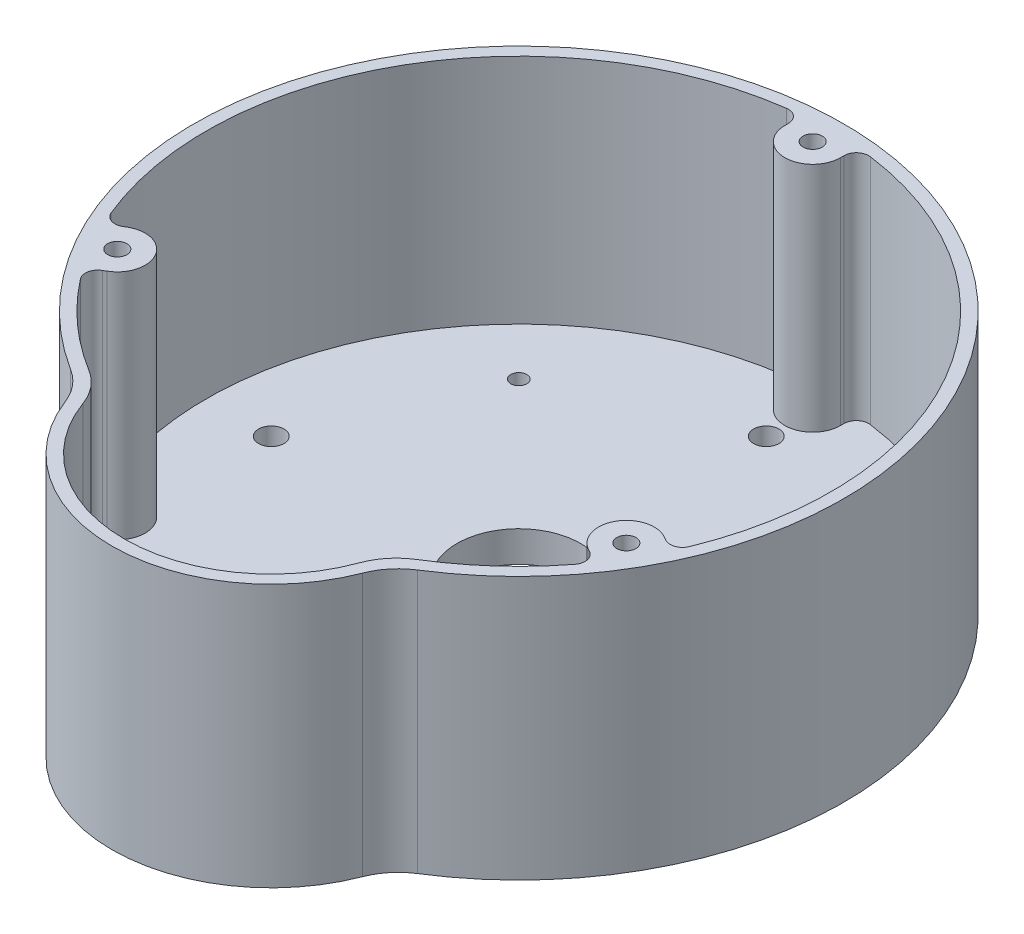
SolidWorks part; units mm, degrees
ref_plane "Plan de face" through (0, 0, 0) normal (0, 0, 1) x (1, 0, 0)
ref_plane "Plan de dessus" through (0, 0, 0) normal (0, 1, 0) x (1, 0, 0)
ref_plane "Plan de droite" through (0, 0, 0) normal (1, 0, 0) x (0, 0, -1)
sketch "Esquisse1" plane through (0, 0, 0) normal (0, 1, 0) x (1, 0, 0)
  line L0 (-51.4386, 28) -> (54.7147, 28) construction
  line L1 (-93.9383, 0) -> (92.9837, 0) construction
  line L2 (0, 84.3142) -> (0, -27.4159) construction
  line L3 (-79.8999, -42) -> (100.4836, -42) construction
  circle A0 centre (0, 0) radius 52.5
  circle A1 centre (0, 40) radius 2.05
  circle A2 centre (40, 0) radius 2.05
  circle A3 centre (0, -40) radius 2.05
  circle A4 centre (-40, 0) radius 2.05
  circle A5 centre (28, 28) radius 1.3
  circle A6 centre (20, -42) radius 1.3
  circle A7 centre (-20, -42) radius 1.3
  circle A8 centre (-28, 28) radius 1.3
  circle A9 centre (0, 0) radius 10
  point P14 (0, 0)
  dimension "D1" = 105
  dimension "D2" = 4.1
  dimension "D7" = 56
  dimension "D9" = 20
  dimension "D10" = 2.6
  dimension "D4" = 40
  dimension "D5" = 28
  dimension "D6" = 42
  dimension "D8" = 40
  dimension "D3" = 4
extrude "Boss.-Extru.2" add sketch "Esquisse1" along normal blind 5
sketch "Esquisse2" plane through (0, 5, 0) normal (0, 1, 0) x (1, 0, 0)
  line L0 (0, 90.2757) -> (0, -93.0238) construction
  line L1 (-4.5, 47.5) -> (-4.5, 50.2991) construction
  line L2 (4.5, 47.5) -> (4.5, 50.2991) construction
  line L3 (0, 0) -> (-88.0909, 50.8593) construction
  line L4 (0, 0) -> (91.089, 52.5902) construction
  line L5 (-4.5, 47.5) -> (-4.5, 48.0625)
  line L6 (4.5, 48.0625) -> (4.5, 47.5)
  line L7 (43.3862, -19.8529) -> (43.8733, -20.1341)
  line L8 (39.3733, -27.9283) -> (38.8862, -27.6471)
  line L9 (-38.8862, -27.6471) -> (-39.3733, -27.9283)
  line L10 (-43.8733, -20.1341) -> (-43.3862, -19.8529)
  circle A0 centre (0, 0) radius 50.5 construction
  circle A1 centre (0, 0) radius 52.5
  circle A2 centre (0, 0) radius 52.5
  circle A3 centre (0, 47.5) radius 4.5
  circle A4 centre (41.1362, -23.75) radius 4.5
  circle A5 centre (-41.1362, -23.75) radius 4.5
  arc A6 (-6.768, 50.0444) -> (-43.7343, 25.25) centre (0, 0) ccw
  arc A7 (6.768, 50.0444) -> (43.7343, 25.25) centre (0, 0) cw
  arc A8 (4.5, 48.0625) -> (6.768, 50.0444) centre (6.5, 48.0625) cw
  arc A9 (-6.768, 50.0444) -> (-4.5, 48.0625) centre (-6.5, 48.0625) cw
  arc A10 (46.7238, -19.1609) -> (43.7343, 25.25) centre (0, 0) ccw
  arc A11 (39.9557, -30.8835) -> (0, -50.5) centre (0, 0) cw
  arc A12 (39.3733, -27.9283) -> (39.9557, -30.8835) centre (38.3733, -29.6604) cw
  arc A13 (46.7238, -19.1609) -> (43.8733, -20.1341) centre (44.8733, -18.4021) cw
  arc A14 (-39.9557, -30.8835) -> (0, -50.5) centre (0, 0) ccw
  arc A15 (-46.7238, -19.1609) -> (-43.7343, 25.25) centre (0, 0) cw
  arc A16 (-43.8733, -20.1341) -> (-46.7238, -19.1609) centre (-44.8733, -18.4021) cw
  arc A17 (-39.9557, -30.8835) -> (-39.3733, -27.9283) centre (-38.3733, -29.6604) cw
  point P28 (0, 0)
  point P51 (0, 0)
  circle M7 centre (0, 0) radius 52.5
  dimension "D2" = 2
  dimension "D3" = 9
  dimension "D4" = 47.5
  dimension "D6" = 60
  dimension "D8" = 2
  dimension "D7" = 60
  dimension "D1" = 0
  dimension "D5" = 3
  dimension "D9" = 3
extrude "Boss.-Extru.3" add sketch "Esquisse2" along normal blind 37.5 contours A5 | A3 | A4 | A14 A17 L9 A5 L10 A16 A15 A6 A9 L5 A3 L6 A8 A7 A10 A13 L7 A4 L8 A12 A11 M7 | A2
sketch "Esquisse3" plane through (0, 42.5, 0) normal (0, 1, 0) x (1, 0, 0)
  circle A0 centre (0, 47.5) radius 3.35
  circle A3 centre (41.1362, -23.75) radius 3.35
  circle A4 centre (-41.1362, -23.75) radius 3.35
  circle A9 centre (0, 0) radius 52.5
  circle A10 centre (0, 0) radius 52.5
  point P13 (0, 0)
  dimension "D2" = 3
  dimension "D3" = 6.7
  dimension "D1" = 0
extrude "Enlèv. mat.-Extru.1" cut sketch "Esquisse3" against normal through all from offset 4 contours A0 | A4 | A3 offset against normal yes
sketch "Esquisse5" plane through (0, 42.5, 0) normal (0, 1, 0) x (1, 0, 0)
  arc A0 (-4.5, 47.5) -> (4.5, 47.5) centre (0, 47.5) ccw construction
  arc A1 (-4.5, 47.5) -> (4.5, 47.5) centre (0, 47.5) ccw
  circle A2 centre (0, 47.5) radius 1.55
  circle A3 centre (41.1362, -23.75) radius 1.55
  circle A4 centre (-41.1362, -23.75) radius 1.55
  point P11 (0, 0)
  dimension "D1" = 3.1
  dimension "D2" = 3
extrude "Enlèv. mat.-Extru.3" cut sketch "Esquisse5" against normal through all contours A4 | A3 | A2
sketch "Esquisse6" plane through (0, 0, 0) normal (0, -1, 0) x (1, 0, 0)
  circle A0 centre (-20, 42) radius 3.75
  circle A1 centre (0, 0) radius 52.5
  circle A3 centre (20, 42) radius 3.75
  circle A4 centre (-28, -28) radius 3.75
  circle A5 centre (28, -28) radius 3.75
  circle A15 centre (0, 0) radius 52.5
  dimension "D2" = 7.5
  dimension "D1" = 0
extrude "Enlèv. mat.-Extru.4" cut sketch "Esquisse6" against normal blind 3 contours A0 | A3 | A5 | A4
sketch "Esquisse7" plane through (0, 0, 0) normal (0, 0, 1) x (1, 0, 0)
  line L0 (0, 56.3049) -> (0, -34.4214) construction
  line L1 (-52.5, 0) -> (52.5, 0) construction
  line L2 (-52.5, 0) -> (52.5, 0)
  line L3 (52.5, 42.5) -> (-52.5, 42.5) construction
  line L4 (52.5, 42.5) -> (-52.5, 42.5)
  line L5 (-25, 42.5) -> (-25, 5)
  line L6 (-25, 5) -> (25, 5)
  line L7 (25, 5) -> (25, 42.5)
  line L8 (-25, 42.5) -> (25, 42.5)
  dimension "D1" = 5
  dimension "D2" = 25
extrude "Enlèv. mat.-Extru.5" cut sketch "Esquisse7" along normal through all contours L0 L8 L5 L6 | L4 L0 L6 L7
sketch "Esquisse8" plane through (0, 0, 0) normal (0, 1, 0) x (1, 0, 0)
  line L0 (0, 4.2422) -> (0, -58.8142) construction
  line L6 (25, -46.1655) -> (25, -43.8777)
  line L7 (25, -46.1655) -> (25, -43.8777)
  line L8 (-38.8862, -27.6471) -> (-39.3733, -27.9283)
  line L9 (-38.8862, -27.6471) -> (-39.3733, -27.9283)
  line L10 (-25, -43.8777) -> (-25, -46.1655)
  line L11 (-25, -43.8777) -> (-25, -46.1655)
  line L12 (39.3733, -27.9283) -> (38.8862, -27.6471)
  line L13 (39.3733, -27.9283) -> (38.8862, -27.6471)
  line L25 (43.3862, -19.8529) -> (43.8733, -20.1341)
  line L26 (43.3862, -19.8529) -> (43.8733, -20.1341)
  line L27 (4.5, 48.0625) -> (4.5, 47.5)
  line L28 (4.5, 48.0625) -> (4.5, 47.5)
  line L29 (-4.5, 47.5) -> (-4.5, 48.0625)
  line L30 (-4.5, 47.5) -> (-4.5, 48.0625)
  line L31 (-43.8733, -20.1341) -> (-43.3862, -19.8529)
  line L32 (-43.8733, -20.1341) -> (-43.3862, -19.8529)
  arc A2 (-25, -46.1655) -> (25, -46.1655) centre (0, -40) ccw
  arc A4 (39.9557, -30.8835) -> (39.3733, -27.9283) centre (38.3733, -29.6604) ccw
  arc A11 (39.9557, -30.8835) -> (39.3733, -27.9283) centre (38.3733, -29.6604) ccw
  arc A12 (-39.3733, -27.9283) -> (-39.9557, -30.8835) centre (-38.3733, -29.6604) ccw
  arc A13 (-39.3733, -27.9283) -> (-39.9557, -30.8835) centre (-38.3733, -29.6604) ccw
  arc A14 (25, -43.8777) -> (39.9557, -30.8835) centre (0, 0) ccw
  arc A15 (25, -43.8777) -> (39.9557, -30.8835) centre (0, 0) ccw
  arc A16 (43.3862, -19.8529) -> (38.8862, -27.6471) centre (41.1362, -23.75) ccw
  arc A17 (43.3862, -19.8529) -> (38.8862, -27.6471) centre (41.1362, -23.75) ccw
  arc A18 (43.8733, -20.1341) -> (46.7238, -19.1609) centre (44.8733, -18.4021) ccw
  arc A19 (43.8733, -20.1341) -> (46.7238, -19.1609) centre (44.8733, -18.4021) ccw
  arc A20 (46.7238, -19.1609) -> (6.768, 50.0444) centre (0, 0) ccw
  arc A21 (46.7238, -19.1609) -> (6.768, 50.0444) centre (0, 0) ccw
  arc A22 (6.768, 50.0444) -> (4.5, 48.0625) centre (6.5, 48.0625) ccw
  arc A23 (6.768, 50.0444) -> (4.5, 48.0625) centre (6.5, 48.0625) ccw
  arc A24 (-4.5, 47.5) -> (4.5, 47.5) centre (0, 47.5) ccw
  arc A25 (-4.5, 47.5) -> (4.5, 47.5) centre (0, 47.5) ccw
  arc A48 (-4.5, 48.0625) -> (-6.768, 50.0444) centre (-6.5, 48.0625) ccw
  arc A49 (-4.5, 48.0625) -> (-6.768, 50.0444) centre (-6.5, 48.0625) ccw
  arc A50 (-6.768, 50.0444) -> (-46.7238, -19.1609) centre (0, 0) ccw
  arc A51 (-6.768, 50.0444) -> (-46.7238, -19.1609) centre (0, 0) ccw
  arc A52 (-46.7238, -19.1609) -> (-43.8733, -20.1341) centre (-44.8733, -18.4021) ccw
  arc A53 (-46.7238, -19.1609) -> (-43.8733, -20.1341) centre (-44.8733, -18.4021) ccw
  arc A54 (-38.8862, -27.6471) -> (-43.3862, -19.8529) centre (-41.1362, -23.75) ccw
  arc A55 (-38.8862, -27.6471) -> (-43.3862, -19.8529) centre (-41.1362, -23.75) ccw
  arc A56 (-39.9557, -30.8835) -> (-25, -43.8777) centre (0, 0) ccw
  arc A57 (-39.9557, -30.8835) -> (-25, -43.8777) centre (0, 0) ccw
  arc A58 (-25, -46.1655) -> (25, -46.1655) centre (0, 0) ccw
  arc A59 (-25, -46.1655) -> (25, -46.1655) centre (0, 0) ccw
  dimension "D2" = 40
  dimension "D1" = 0
extrude "Boss.-Extru.5" add sketch "Esquisse8" along normal blind 5
sketch "Esquisse11" plane through (0, 5, 0) normal (0, 1, 0) x (1, 0, 0)
  line L0 (0, 0) -> (0, -73.5524) construction
  line L8 (25, -46.1655) -> (25, -43.8777)
  line L9 (39.3733, -27.9283) -> (38.8862, -27.6471)
  line L10 (43.3862, -19.8529) -> (43.8733, -20.1341)
  line L11 (4.5, 48.0625) -> (4.5, 47.5)
  line L12 (-4.5, 47.5) -> (-4.5, 48.0625)
  line L13 (-43.8733, -20.1341) -> (-43.3862, -19.8529)
  line L14 (-38.8862, -27.6471) -> (-39.3733, -27.9283)
  line L15 (-25, -43.8777) -> (-25, -46.1655)
  line L16 (25, -46.1655) -> (25, -43.8777)
  line L17 (39.3733, -27.9283) -> (38.8862, -27.6471)
  line L18 (43.3862, -19.8529) -> (43.8733, -20.1341)
  line L19 (4.5, 48.0625) -> (4.5, 47.5)
  line L20 (-4.5, 47.5) -> (-4.5, 48.0625)
  line L21 (-43.8733, -20.1341) -> (-43.3862, -19.8529)
  line L22 (-38.8862, -27.6471) -> (-39.3733, -27.9283)
  line L23 (-25, -43.8777) -> (-25, -46.1655)
  arc A0 (-25, -43.8777) -> (25, -43.8777) centre (0, 0) ccw
  arc A1 (-23.2531, -44.8279) -> (23.2531, -44.8279) centre (0, -40) ccw
  arc A14 (25, -43.8777) -> (39.9557, -30.8835) centre (0, 0) ccw
  arc A15 (39.9557, -30.8835) -> (39.3733, -27.9283) centre (38.3733, -29.6604) ccw
  arc A16 (43.3862, -19.8529) -> (38.8862, -27.6471) centre (41.1362, -23.75) ccw
  arc A17 (43.8733, -20.1341) -> (46.7238, -19.1609) centre (44.8733, -18.4021) ccw
  arc A18 (46.7238, -19.1609) -> (6.768, 50.0444) centre (0, 0) ccw
  arc A19 (6.768, 50.0444) -> (4.5, 48.0625) centre (6.5, 48.0625) ccw
  arc A20 (-4.5, 47.5) -> (4.5, 47.5) centre (0, 47.5) ccw
  arc A21 (-4.5, 48.0625) -> (-6.768, 50.0444) centre (-6.5, 48.0625) ccw
  arc A22 (-6.768, 50.0444) -> (-46.7238, -19.1609) centre (0, 0) ccw
  arc A23 (-46.7238, -19.1609) -> (-43.8733, -20.1341) centre (-44.8733, -18.4021) ccw
  arc A24 (-38.8862, -27.6471) -> (-43.3862, -19.8529) centre (-41.1362, -23.75) ccw
  arc A25 (-39.3733, -27.9283) -> (-39.9557, -30.8835) centre (-38.3733, -29.6604) ccw
  arc A26 (-39.9557, -30.8835) -> (-25, -43.8777) centre (0, 0) ccw
  arc A27 (-25, -46.1655) -> (25, -46.1655) centre (0, -40) ccw
  arc A28 (25, -43.8777) -> (39.9557, -30.8835) centre (0, 0) ccw
  arc A29 (39.9557, -30.8835) -> (39.3733, -27.9283) centre (38.3733, -29.6604) ccw
  arc A30 (43.3862, -19.8529) -> (38.8862, -27.6471) centre (41.1362, -23.75) ccw
  arc A31 (43.8733, -20.1341) -> (46.7238, -19.1609) centre (44.8733, -18.4021) ccw
  arc A32 (46.7238, -19.1609) -> (6.768, 50.0444) centre (0, 0) ccw
  arc A33 (6.768, 50.0444) -> (4.5, 48.0625) centre (6.5, 48.0625) ccw
  arc A34 (-4.5, 47.5) -> (4.5, 47.5) centre (0, 47.5) ccw
  arc A35 (-4.5, 48.0625) -> (-6.768, 50.0444) centre (-6.5, 48.0625) ccw
  arc A36 (-6.768, 50.0444) -> (-46.7238, -19.1609) centre (0, 0) ccw
  arc A37 (-46.7238, -19.1609) -> (-43.8733, -20.1341) centre (-44.8733, -18.4021) ccw
  arc A38 (-38.8862, -27.6471) -> (-43.3862, -19.8529) centre (-41.1362, -23.75) ccw
  arc A39 (-39.3733, -27.9283) -> (-39.9557, -30.8835) centre (-38.3733, -29.6604) ccw
  arc A40 (-39.9557, -30.8835) -> (-25, -43.8777) centre (0, 0) ccw
  arc A41 (-25, -46.1655) -> (25, -46.1655) centre (0, -40) ccw
  line M24 (25, -46.1655) -> (25, -43.8777)
  line M44 (-25, -43.8777) -> (-25, -46.1655)
  arc M45 (-25, -46.1655) -> (25, -46.1655) centre (0, -40) ccw
  dimension "D2" = 2
  dimension "D1" = 0
extrude "Boss.-Extru.9" add sketch "Esquisse11" along normal blind 37.5 contours L0 A1 A0 M44 M45 | A1 L0 A41 A0 M24
fillet "Congé1" radius 10 4 edges at (-23.2531, 23.75, 44.8279) (23.2531, 23.75, 44.8279) (25, 21.25, 46.1655) (-25, 21.25, 46.1655)
